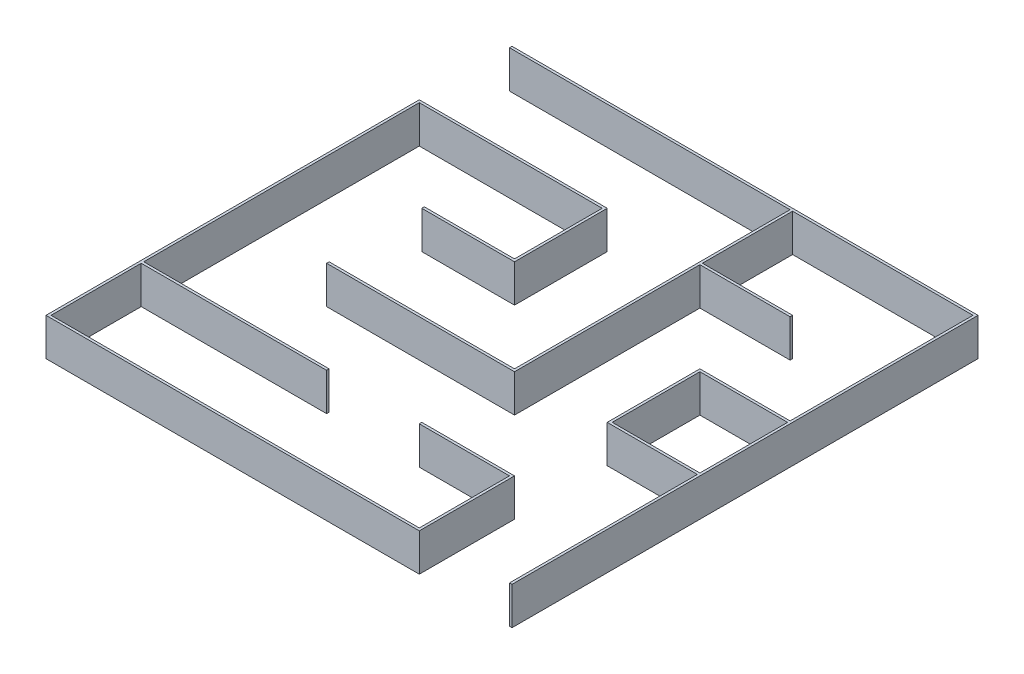
SolidWorks part; units mm, degrees
ref_plane "Front Plane" through (0, 0, 0) normal (0, 0, 1) x (1, 0, 0)
ref_plane "Top Plane" through (0, 0, 0) normal (0, 1, 0) x (1, 0, 0)
ref_plane "Right Plane" through (0, 0, 0) normal (1, 0, 0) x (0, 0, -1)
sketch "Sketch2" plane through (0, 0, 0) normal (0, 1, 0) x (1, 0, 0)
  line L0 (150, 757.4912) -> (150, 397.4912)
  line L5 (890, 767.4912) -> (140, 767.4912) construction
  line L6 (890, 757.4912) -> (140, 757.4912) construction
  line L7 (-2900, 2247.4912) -> (2000, 2247.4912) construction
  line L8 (-2900, 2247.4912) -> (-2900, -202.5088) construction
  line L9 (-2900, -202.5088) -> (2000, -202.5088) construction
  line L10 (2000, 2247.4912) -> (2000, -202.5088) construction
  line L11 (2000, 2247.4912) -> (140, 2247.4912) construction
  line L12 (2000, 2247.4912) -> (2000, 387.4912) construction
  line L13 (2000, 387.4912) -> (140, 387.4912) construction
  line L14 (140, 2247.4912) -> (140, 387.4912) construction
  line L15 (140, 2247.4912) -> (-1360, 2247.4912) construction
  line L16 (140, 2247.4912) -> (140, 387.4912) construction
  line L17 (140, 387.4912) -> (-1360, 387.4912) construction
  line L18 (-1360, 2247.4912) -> (-1360, 387.4912) construction
  line L24 (150, 1867.4912) -> (150, 397.4912) construction
  line L29 (0, 1877.4912) -> (2233.1632, 1877.4912) construction
  line L30 (0, 1507.4912) -> (2233.1632, 1507.4912) construction
  line L31 (0, 1137.4912) -> (2233.1632, 1137.4912) construction
  line L32 (0, 767.4912) -> (2233.1632, 767.4912) construction
  line L33 (520, 322.8834) -> (520, 2769.7829) construction
  line L34 (890, 322.8834) -> (890, 2730.1034) construction
  line L35 (1260, 322.8834) -> (1260, 2730.1034) construction
  line L36 (1630, 322.8834) -> (1630, 2730.1034) construction
  line L37 (2000, 387.4912) -> (2000, 2247.4912)
  line L38 (2000, 2247.4912) -> (140, 2247.4912)
  line L39 (140, 1877.4912) -> (140, 387.4912)
  line L40 (140, 387.4912) -> (1630, 387.4912)
  line L41 (1990, 1507.4912) -> (1630, 1507.4912)
  line L42 (1630, 1507.4912) -> (1630, 1137.4912)
  line L43 (1630, 1137.4912) -> (1990, 1137.4912)
  line L44 (1260, 2237.4912) -> (1260, 1137.4912)
  line L45 (1260, 1137.4912) -> (520, 1137.4912)
  line L46 (1270, 1877.4912) -> (1630, 1877.4912)
  line L47 (1260, 767.4912) -> (1630, 767.4912)
  line L48 (1630, 767.4912) -> (1630, 387.4912)
  line L49 (890, 767.4912) -> (150, 767.4912)
  line L50 (140, 1877.4912) -> (890, 1877.4912)
  line L51 (890, 1877.4912) -> (890, 1507.4912)
  line L52 (890, 1507.4912) -> (520, 1507.4912)
  line L53 (1260, 757.4912) -> (1620, 757.4912)
  line L54 (1620, 757.4912) -> (1620, 397.4912)
  line L55 (150, 397.4912) -> (1620, 397.4912)
  line L56 (150, 1867.4912) -> (150, 767.4912)
  line L57 (150, 1867.4912) -> (880, 1867.4912)
  line L58 (880, 1867.4912) -> (880, 1517.4912)
  line L59 (880, 1517.4912) -> (520, 1517.4912)
  line L60 (890, 757.4912) -> (150, 757.4912)
  line L61 (1990, 387.4912) -> (1990, 1137.4912)
  line L62 (1990, 2237.4912) -> (1270, 2237.4912)
  line L63 (1270, 2237.4912) -> (1270, 1877.4912)
  line L64 (1270, 1127.4912) -> (520, 1127.4912)
  line L65 (1270, 1867.4912) -> (1630, 1867.4912)
  line L66 (1990, 1497.4912) -> (1640, 1497.4912)
  line L67 (1640, 1497.4912) -> (1640, 1147.4912)
  line L68 (1640, 1147.4912) -> (1990, 1147.4912)
  line L69 (140, 2237.4912) -> (140, 2247.4912)
  line L70 (520, 1517.4912) -> (520, 1507.4912)
  line L71 (520, 1137.4912) -> (520, 1127.4912)
  line L72 (890, 757.4912) -> (890, 767.4912)
  line L73 (1260, 767.4912) -> (1260, 757.4912)
  line L74 (1630, 1877.4912) -> (1630, 1867.4912)
  line L75 (1990, 387.4912) -> (2000, 387.4912)
  line L76 (1260, 2237.4912) -> (140, 2237.4912)
  line L77 (1260, 1877.4912) -> (1630, 1877.4912) construction
  line L78 (1260, 1867.4912) -> (1630, 1867.4912) construction
  line L79 (1270, 2247.4912) -> (1270, 1127.4912) construction
  line L80 (1260, 2247.4912) -> (1260, 1137.4912) construction
  line L81 (1270, 1867.4912) -> (1270, 1127.4912)
  line L82 (1990, 2237.4912) -> (140, 2237.4912) construction
  line L83 (1990, 1507.4912) -> (1990, 2237.4912)
  line L84 (2000, 1507.4912) -> (1630, 1507.4912) construction
  line L85 (2000, 1497.4912) -> (1640, 1497.4912) construction
  line L86 (1990, 1147.4912) -> (1990, 1497.4912)
  line L87 (1990, 387.4912) -> (1990, 2237.4912) construction
  line L88 (1630, 1137.4912) -> (2000, 1137.4912) construction
  line L89 (1640, 1147.4912) -> (2000, 1147.4912) construction
  dimension "D3" = 4900
  dimension "D4" = 2450
  dimension "D6" = 1860
  dimension "D8" = 1500
  dimension "D11" = 370
  dimension "D12" = 370
  dimension "D13" = 370
  dimension "D14" = 370
  dimension "D15" = 370
  dimension "D16" = 370
  dimension "D17" = 370
  dimension "D18" = 370
  dimension "D20" = 10
  dimension "D21" = 10
  dimension "D22" = 10
  dimension "D23" = 10
  dimension "D24" = 10
extrude "Boss-Extrude3" add sketch "Sketch2" along normal blind 150 contours L56 L49 L72 L60 L0 L55 L54 L53 L73 L47 L48 L40 L39 L50 L51 L52 L70 L59 L58 L57 | L61 L43 L42 L41 L83 L62 L63 L46 L74 L65 L81 L64 L71 L45 L44 L76 L69 L38 L37 L75 | L66 L67 L68 L86
